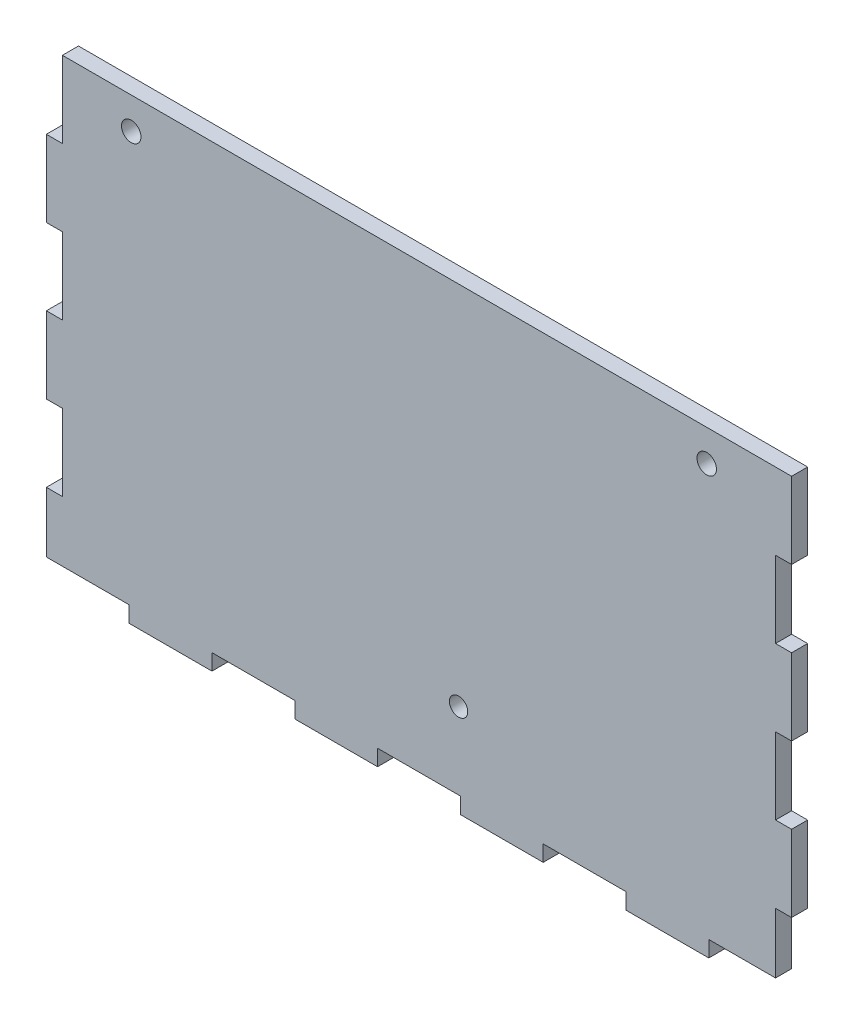
SolidWorks part; units mm, degrees
material "Acrylic (Medium-high impact)"
ref_plane "Front Plane" through (0, 0, 0) normal (0, 0, 1) x (1, 0, 0)
ref_plane "Top Plane" through (0, 0, 0) normal (0, 1, 0) x (1, 0, 0)
ref_plane "Right Plane" through (0, 0, 0) normal (1, 0, 0) x (0, 0, -1)
sketch "Sketch1" plane through (0, 0, 0) normal (0, 0, 1) x (1, 0, 0)
  line L1 (0, 0) -> (130, 0)
  line L2 (0, 0) -> (0, 80)
  line L3 (0, 80) -> (130, 80)
  line L4 (130, 0) -> (130, 80)
  dimension "D1" = 130
  dimension "D2" = 80
extrude "Boss-Extrude1" add sketch "Sketch1" along normal blind 2.8
sketch "Sketch2" plane through (0, 0, 2.8) normal (0, 0, 1) x (1, 0, 0)
  line L61 (14.4444, 2.8) -> (28.8889, 2.8) construction
  line L62 (0, 0) -> (14.4444, 0)
  line L67 (0, 0) -> (0, 2.8)
  line L72 (0, 2.8) -> (14.4444, 2.8)
  line L77 (14.4444, 0) -> (14.4444, 2.8)
  line L97 (28.8889, 0) -> (28.8889, 2.8)
  line L98 (28.8889, 0) -> (43.3333, 0)
  line L107 (43.3333, 0) -> (43.3333, 2.8)
  line L115 (28.8889, 2.8) -> (43.3333, 2.8)
  line L117 (43.3333, 2.8) -> (57.7778, 2.8) construction
  line L123 (57.7778, 0) -> (57.7778, 2.8)
  line L128 (57.7778, 0) -> (72.2222, 0)
  line L129 (72.2222, 0) -> (72.2222, 2.8)
  line L131 (57.7778, 2.8) -> (72.2222, 2.8)
  line L132 (72.2222, 2.8) -> (86.6667, 2.8) construction
  line L133 (86.6667, 0) -> (86.6667, 2.8)
  line L134 (86.6667, 0) -> (101.1111, 0)
  line L135 (101.1111, 0) -> (101.1111, 2.8)
  line L136 (86.6667, 2.8) -> (101.1111, 2.8)
  line L137 (101.1111, 2.8) -> (115.5556, 2.8) construction
  line L138 (115.5556, 0) -> (115.5556, 2.8)
  line L139 (115.5556, 0) -> (130, 0)
  line L142 (130, 0) -> (130, 80) construction
  line L143 (0, 80) -> (0, 0) construction
  line L144 (0, 13.3333) -> (2.8, 13.3333)
  line L145 (0, 13.3333) -> (0, 26.6667)
  line L146 (130, 2.8) -> (144.4444, 2.8) construction
  line L147 (0, 26.6667) -> (2.8, 26.6667)
  line L148 (2.8, 13.3333) -> (2.8, 26.6667)
  line L149 (2.8, 13.3333) -> (2.8, 0) construction
  line L150 (0, 40) -> (0, 53.3333)
  line L151 (0, 40) -> (2.8, 40)
  line L152 (2.8, 40) -> (2.8, 53.3333)
  line L153 (0, 53.3333) -> (2.8, 53.3333)
  line L154 (2.8, 40) -> (2.8, 26.6667) construction
  line L155 (0, 66.6667) -> (0, 80)
  line L156 (0, 66.6667) -> (2.8, 66.6667)
  line L157 (2.8, 66.6667) -> (2.8, 80)
  line L158 (0, 80) -> (2.8, 80)
  line L159 (2.8, 66.6667) -> (2.8, 53.3333) construction
  line L160 (130, 80) -> (0, 80) construction
  line L161 (127.2, 80) -> (127.2, 66.6667) construction
  line L162 (127.2, 40) -> (127.2, 26.6667)
  line L163 (127.2, 66.6667) -> (130, 66.6667)
  line L164 (127.2, 66.6667) -> (127.2, 53.3333)
  line L165 (127.2, 53.3333) -> (130, 53.3333)
  line L166 (130, 66.6667) -> (130, 53.3333)
  line L167 (127.2, 40) -> (130, 40)
  line L168 (130, 40) -> (130, 26.6667)
  line L169 (127.2, 26.6667) -> (130, 26.6667)
  line L170 (127.2, 53.3333) -> (127.2, 40) construction
  line L172 (127.2, 13.3333) -> (130, 13.3333)
  line L173 (130, 13.3333) -> (130, 0)
  line L175 (127.2, 26.6667) -> (127.2, 13.3333) construction
  line L183 (115.5556, 2.8) -> (130, 2.8) [skipped]
  line L184 (130, 0) -> (130, 2.8) [skipped]
  line L185 (127.2, 13.3333) -> (127.2, 2.8)
  line L186 (127.2, 2.8) -> (115.5556, 2.8)
  line L187 (127.2, 0) -> (130, 0) [skipped]
  line L188 (127.2, 13.3333) -> (127.2, 0) [skipped]
  dimension "D2" = 2.8
  dimension "D4" = 2.8
  dimension "D6" = 2.8
  dimension "D1" = 5
  dimension "D3" = 3
  dimension "D5" = 3
extrude "Cut-Extrude1" cut sketch "Sketch2" against normal through all
sketch "Sketch3" plane through (0, 0, 2.8) normal (0, 0, 1) x (1, 0, 0)
  line L0 (0, 66.6667) -> (0, 53.3333) construction
  line L1 (130, 80) -> (2.8, 80) construction
  line L2 (0, 66.6667) -> (130, 66.6667) construction
  line L3 (65, 66.6667) -> (65, 50066.6667) construction
  circle A0 centre (14.8, 74.5) radius 1.7
  circle A1 centre (115.2, 74.5) radius 1.7
  point P10 (65, 66.6667)
  dimension "D1" = 3.4
  dimension "D2" = 14.8
  dimension "D3" = 5.5
extrude "Cut-Extrude2" cut sketch "Sketch3" against normal up to next
sketch "Sketch4" plane through (0, 0, 0) normal (0, 0, -1) x (-1, 0, 0)
  line L0 (-130, 13.3333) -> (-130, 26.6667) construction
  line L4 (-72.2222, 2.8) -> (-57.7778, 2.8) construction
  circle A0 centre (-71.91, 16.16) radius 1.6
  dimension "D2" = 3.2
  dimension "D1" = 58.09
  dimension "D3" = 13.36
extrude "Tuning driver hole" cut sketch "Sketch4" against normal up to next
other "Width tolerance" face at (128.6, 53.3333, 1.4) face at (128.6, 26.6667, 1.4) face at (128.6, 13.3333, 1.4) face at (128.6, 40, 1.4) face at (128.6, 66.6667, 1.4) face at (115.5556, 1.4, 1.4) face at (86.6667, 1.4, 1.4) face at (57.7778, 1.4, 1.4) face at (28.8889, 1.4, 1.4) face at (14.4444, 1.4, 1.4) face at (43.3333, 1.4, 1.4) face at (72.2222, 1.4, 1.4) face at (101.1111, 1.4, 1.4) face at (1.4, 26.6667, 1.4) face at (1.4, 13.3333, 1.4) face at (1.4, 40, 1.4) face at (1.4, 53.3333, 1.4) face at (1.4, 66.6667, 1.4) parameters "D1"=0
equation "\"wall_thickness\" = 2.8mm"
equation "\"D1@Boss-Extrude1\"=\"wall_thickness\""
equation "\"slot_width_tolerance\"= 0.0mm"
equation "\"slot_depth\"= 2.8mm"
equation "\"D2@Sketch2\"=\"slot_depth\""
equation "\"D4@Sketch2\"=\"slot_depth\""
equation "\"D6@Sketch2\"=\"slot_depth\""
equation "\"D2@Sketch3\"=12.00mm+\"slot_depth\""
equation "\"D1@Width tolerance\" = \"slot_width_tolerance\""
